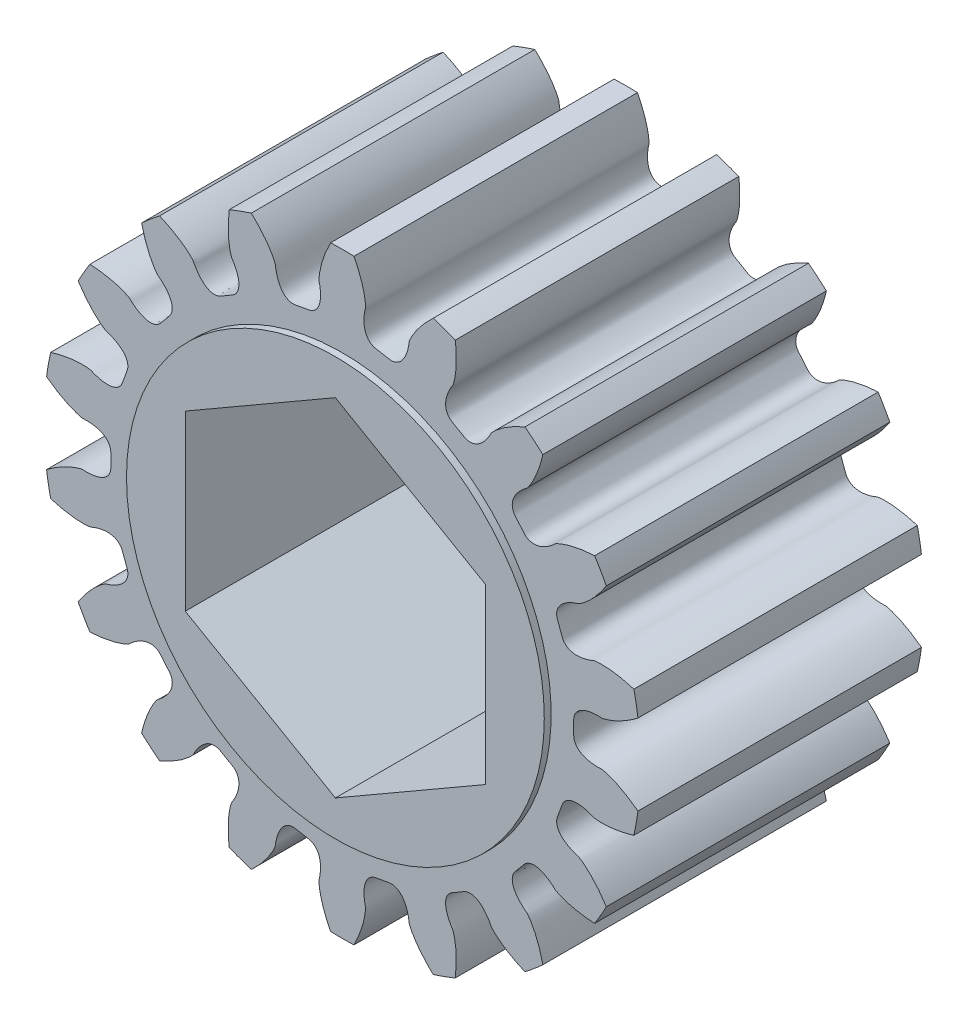
SolidWorks part; units mm, degrees
material "7075-T6 (SN)"
ref_plane "Front Plane" through (0, 0, 0) normal (0, 0, 1) x (1, 0, 0)
ref_plane "Top Plane" through (0, 0, 0) normal (0, 1, 0) x (1, 0, 0)
ref_plane "Right Plane" through (0, 0, 0) normal (1, 0, 0) x (0, 0, -1)
ref_plane "Plane1" through (0, 0, 6.0325) normal (0, 0, 1) x (1, 0, 0)
sketch "Sketch1" plane through (0, 0, 6.0325) normal (0, 0, 1) x (1, 0, 0)
  arc A0 (12.411, -2.694) -> (12.5839, -1.7132) centre (0, 0) ccw
  arc A1 (12.5839, 1.7132) -> (12.411, 2.694) centre (0, 0) ccw
  arc A2 (11.239, 5.9139) -> (10.7411, 6.7764) centre (0, 0) ccw
  arc A3 (8.5386, 9.4012) -> (7.7757, 10.0414) centre (0, 0) ccw
  arc A4 (4.8082, 11.7546) -> (3.8724, 12.0952) centre (0, 0) ccw
  arc A5 (0.498, 12.6902) -> (-0.498, 12.6902) centre (0, 0) ccw
  arc A6 (-3.8724, 12.0952) -> (-4.8082, 11.7546) centre (0, 0) ccw
  arc A7 (-7.7757, 10.0414) -> (-8.5386, 9.4012) centre (0, 0) ccw
  arc A8 (-10.7411, 6.7764) -> (-11.239, 5.9139) centre (0, 0) ccw
  arc A9 (-12.411, 2.694) -> (-12.5839, 1.7132) centre (0, 0) ccw
  arc A10 (-12.5839, -1.7132) -> (-12.411, -2.694) centre (0, 0) ccw
  arc A11 (-11.239, -5.9139) -> (-10.7411, -6.7764) centre (0, 0) ccw
  arc A12 (-8.5386, -9.4012) -> (-7.7757, -10.0414) centre (0, 0) ccw
  arc A13 (-4.8082, -11.7546) -> (-3.8724, -12.0952) centre (0, 0) ccw
  arc A14 (-0.498, -12.6902) -> (0.498, -12.6902) centre (0, 0) ccw
  arc A15 (3.8724, -12.0952) -> (4.8082, -11.7546) centre (0, 0) ccw
  arc A16 (7.7757, -10.0414) -> (8.5386, -9.4012) centre (0, 0) ccw
  arc A17 (10.7411, -6.7764) -> (11.239, -5.9139) centre (0, 0) ccw
  spline S0 degree 3 poles (11.239, -5.9139) (11.1509, -5.7775) (11.0298, -5.6051) (10.8706, -5.4047) (10.783, -5.3007) (10.6983, -5.2057) (10.6171, -5.1195) (10.5396, -5.0419) (10.4664, -4.9725) (10.3977, -4.911) (10.3341, -4.8571) (10.2759, -4.8106) (10.2233, -4.771) (10.1769, -4.7378) (10.1275, -4.7053) (10.0518, -4.6541) (9.95, -4.6355) (9.8549, -4.5968) (9.7835, -4.5675) (9.7159, -4.5362) (9.6517, -4.5038) (9.5908, -4.4699) (9.5333, -4.4347) (9.479, -4.3981) (9.4279, -4.3599) (9.3799, -4.3199) (9.3348, -4.2779) (9.2928, -4.2333) (9.2539, -4.1857) (9.2182, -4.1342) (9.1862, -4.078) (9.1588, -4.016) (9.1377, -3.9474) (9.125, -3.8716) (9.1237, -3.7895) (9.1359, -3.7108) (9.1798, -3.5695) (9.267, -3.3729) (9.3266, -3.1663) (9.3837, -3.0298) (9.425, -2.9616) (9.4787, -2.8996) (9.5372, -2.8497) (9.5975, -2.8107) (9.6583, -2.7808) (9.719, -2.7583) (9.7794, -2.7419) (9.8398, -2.7304) (9.9007, -2.7233) (9.9622, -2.72) (10.0247, -2.7203) (10.0884, -2.7238) (10.1535, -2.7307) (10.2202, -2.7407) (10.2886, -2.7539) (10.3586, -2.7703) (10.4305, -2.7899) (10.504, -2.8133) (10.6018, -2.8447) (10.6917, -2.8959) (10.7827, -2.9054) (10.8413, -2.9122) (10.8982, -2.9166) (10.9639, -2.9201) (11.0385, -2.9219) (11.1219, -2.9215) (11.2139, -2.9185) (11.3147, -2.9124) (11.4239, -2.9027) (11.5416, -2.889) (11.6675, -2.8706) (11.8014, -2.8472) (12.0522, -2.7961) (12.2559, -2.7418) (12.411, -2.694) knots 0 0 0 0 0.068568 0.088955 0.108106 0.126021 0.142701 0.158145 0.172354 0.185328 0.197065 0.207567 0.216834 0.224865 0.231661 0.241836 0.263156 0.274398 0.285253 0.295736 0.305862 0.315655 0.325139 0.334346 0.343315 0.352092 0.360737 0.369325 0.377945 0.38671 0.395752 0.405223 0.415278 0.426045 0.437578 0.449793 0.459544 0.5 0.540456 0.550207 0.562422 0.573955 0.584722 0.594777 0.604248 0.61329 0.622055 0.630675 0.639263 0.647908 0.656685 0.665654 0.674861 0.684345 0.694138 0.704264 0.714747 0.725602 0.736844 0.758164 0.768339 0.775135 0.783166 0.792433 0.802935 0.814672 0.827646 0.841855 0.857299 0.873979 0.891894 0.911045 0.931432 1 1 1 1
  spline S1 degree 3 poles (12.5839, -1.7132) (12.4545, -1.6153) (12.2817, -1.4946) (12.0635, -1.3608) (11.9456, -1.293) (11.8336, -1.2327) (11.7278, -1.1795) (11.6284, -1.133) (11.5359, -1.0929) (11.4503, -1.0586) (11.3721, -1.0297) (11.3015, -1.0059) (11.2385, -0.9867) (11.1836, -0.9714) (11.1261, -0.9577) (11.0374, -0.9355) (10.9354, -0.9529) (10.8328, -0.949) (10.7557, -0.9458) (10.6815, -0.9396) (10.61, -0.9311) (10.5412, -0.9201) (10.4751, -0.9067) (10.4116, -0.8909) (10.3505, -0.8724) (10.2917, -0.8513) (10.235, -0.8272) (10.1803, -0.7997) (10.1274, -0.7682) (10.0762, -0.7321) (10.027, -0.6902) (9.9801, -0.6413) (9.9367, -0.584) (9.8988, -0.5172) (9.8696, -0.4405) (9.8541, -0.3623) (9.847, -0.2145) (9.8618, 0) (9.847, 0.2145) (9.8541, 0.3623) (9.8696, 0.4405) (9.8988, 0.5172) (9.9367, 0.584) (9.9801, 0.6413) (10.027, 0.6902) (10.0762, 0.7321) (10.1274, 0.7682) (10.1803, 0.7997) (10.235, 0.8272) (10.2917, 0.8513) (10.3505, 0.8724) (10.4116, 0.8909) (10.4751, 0.9067) (10.5412, 0.9201) (10.61, 0.9311) (10.6815, 0.9396) (10.7557, 0.9458) (10.8328, 0.949) (10.9354, 0.9529) (11.0374, 0.9355) (11.1261, 0.9577) (11.1836, 0.9714) (11.2385, 0.9867) (11.3015, 1.0059) (11.3721, 1.0297) (11.4503, 1.0586) (11.5359, 1.0929) (11.6284, 1.133) (11.7278, 1.1795) (11.8336, 1.2327) (11.9456, 1.293) (12.0635, 1.3608) (12.2817, 1.4946) (12.4545, 1.6153) (12.5839, 1.7132) knots 0 0 0 0 0.068568 0.088955 0.108106 0.126021 0.142701 0.158145 0.172354 0.185328 0.197065 0.207567 0.216834 0.224865 0.231661 0.241836 0.263156 0.274398 0.285253 0.295736 0.305862 0.315655 0.325139 0.334346 0.343315 0.352092 0.360737 0.369325 0.377945 0.38671 0.395752 0.405223 0.415278 0.426045 0.437578 0.449793 0.459544 0.5 0.540456 0.550207 0.562422 0.573955 0.584722 0.594777 0.604248 0.61329 0.622055 0.630675 0.639263 0.647908 0.656685 0.665654 0.674861 0.684345 0.694138 0.704264 0.714747 0.725602 0.736844 0.758164 0.768339 0.775135 0.783166 0.792433 0.802935 0.814672 0.827646 0.841855 0.857299 0.873979 0.891894 0.911045 0.931432 1 1 1 1
  spline S2 degree 3 poles (12.411, 2.694) (12.2559, 2.7418) (12.0522, 2.7961) (11.8014, 2.8472) (11.6675, 2.8706) (11.5416, 2.889) (11.4239, 2.9027) (11.3147, 2.9124) (11.2139, 2.9185) (11.1219, 2.9215) (11.0385, 2.9219) (10.9639, 2.9201) (10.8982, 2.9166) (10.8413, 2.9122) (10.7827, 2.9054) (10.6917, 2.8959) (10.6018, 2.8447) (10.504, 2.8133) (10.4305, 2.7899) (10.3586, 2.7703) (10.2886, 2.7539) (10.2202, 2.7407) (10.1535, 2.7307) (10.0884, 2.7238) (10.0247, 2.7203) (9.9622, 2.72) (9.9007, 2.7233) (9.8398, 2.7304) (9.7794, 2.7419) (9.719, 2.7583) (9.6583, 2.7808) (9.5975, 2.8107) (9.5372, 2.8497) (9.4787, 2.8996) (9.425, 2.9616) (9.3837, 3.0298) (9.3266, 3.1663) (9.267, 3.3729) (9.1798, 3.5695) (9.1359, 3.7108) (9.1237, 3.7895) (9.125, 3.8716) (9.1377, 3.9474) (9.1588, 4.016) (9.1862, 4.078) (9.2182, 4.1342) (9.2539, 4.1857) (9.2928, 4.2333) (9.3348, 4.2779) (9.3799, 4.3199) (9.4279, 4.3599) (9.479, 4.3981) (9.5333, 4.4347) (9.5908, 4.4699) (9.6517, 4.5038) (9.7159, 4.5362) (9.7835, 4.5675) (9.8549, 4.5968) (9.95, 4.6355) (10.0518, 4.6541) (10.1275, 4.7053) (10.1769, 4.7378) (10.2233, 4.771) (10.2759, 4.8106) (10.3341, 4.8571) (10.3977, 4.911) (10.4664, 4.9725) (10.5396, 5.0419) (10.6171, 5.1195) (10.6983, 5.2057) (10.783, 5.3007) (10.8706, 5.4047) (11.0298, 5.6051) (11.1509, 5.7775) (11.239, 5.9139) knots 0 0 0 0 0.068568 0.088955 0.108106 0.126021 0.142701 0.158145 0.172354 0.185328 0.197065 0.207567 0.216834 0.224865 0.231661 0.241836 0.263156 0.274398 0.285253 0.295736 0.305862 0.315655 0.325139 0.334346 0.343315 0.352092 0.360737 0.369325 0.377945 0.38671 0.395752 0.405223 0.415278 0.426045 0.437578 0.449793 0.459544 0.5 0.540456 0.550207 0.562422 0.573955 0.584722 0.594777 0.604248 0.61329 0.622055 0.630675 0.639263 0.647908 0.656685 0.665654 0.674861 0.684345 0.694138 0.704264 0.714747 0.725602 0.736844 0.758164 0.768339 0.775135 0.783166 0.792433 0.802935 0.814672 0.827646 0.841855 0.857299 0.873979 0.891894 0.911045 0.931432 1 1 1 1
  spline S3 degree 3 poles (10.7411, 6.7764) (10.579, 6.7682) (10.369, 6.7496) (10.1159, 6.7118) (9.982, 6.688) (9.8574, 6.6622) (9.7422, 6.6349) (9.6362, 6.6066) (9.5395, 6.5779) (9.4519, 6.5492) (9.3735, 6.521) (9.304, 6.4939) (9.2434, 6.4682) (9.1915, 6.4445) (9.1387, 6.418) (9.0565, 6.3781) (8.9895, 6.2992) (8.9084, 6.2362) (8.8473, 6.1891) (8.7864, 6.1461) (8.7262, 6.1067) (8.6665, 6.0709) (8.6073, 6.0387) (8.5484, 6.01) (8.4897, 5.9848) (8.4311, 5.9632) (8.3722, 5.9453) (8.3126, 5.9312) (8.2518, 5.9212) (8.1894, 5.916) (8.1248, 5.9165) (8.0574, 5.9238) (7.9873, 5.9398) (7.9154, 5.9667) (7.8437, 6.0066) (7.7815, 6.0565) (7.6812, 6.1652) (7.5546, 6.339) (7.4054, 6.4939) (7.3157, 6.6116) (7.2774, 6.6815) (7.2505, 6.759) (7.2365, 6.8346) (7.2329, 6.9064) (7.2374, 6.974) (7.2483, 7.0377) (7.2642, 7.0983) (7.2845, 7.1563) (7.3088, 7.2126) (7.3367, 7.2675) (7.3681, 7.3215) (7.4031, 7.3749) (7.4416, 7.4279) (7.4836, 7.4806) (7.5292, 7.5332) (7.5785, 7.5857) (7.6314, 7.6382) (7.6884, 7.6901) (7.7645, 7.7591) (7.8538, 7.8113) (7.9074, 7.8854) (7.9427, 7.9328) (7.975, 7.9798) (8.0108, 8.035) (8.0497, 8.0987) (8.091, 8.1711) (8.1345, 8.2523) (8.1796, 8.3426) (8.2258, 8.442) (8.2727, 8.5508) (8.3198, 8.669) (8.3665, 8.7967) (8.4476, 9.0394) (8.5024, 9.243) (8.5386, 9.4012) knots 0 0 0 0 0.068568 0.088955 0.108106 0.126021 0.142701 0.158145 0.172354 0.185328 0.197065 0.207567 0.216834 0.224865 0.231661 0.241836 0.263156 0.274398 0.285253 0.295736 0.305862 0.315655 0.325139 0.334346 0.343315 0.352092 0.360737 0.369325 0.377945 0.38671 0.395752 0.405223 0.415278 0.426045 0.437578 0.449793 0.459544 0.5 0.540456 0.550207 0.562422 0.573955 0.584722 0.594777 0.604248 0.61329 0.622055 0.630675 0.639263 0.647908 0.656685 0.665654 0.674861 0.684345 0.694138 0.704264 0.714747 0.725602 0.736844 0.758164 0.768339 0.775135 0.783166 0.792433 0.802935 0.814672 0.827646 0.841855 0.857299 0.873979 0.891894 0.911045 0.931432 1 1 1 1
  spline S4 degree 3 poles (7.7757, 10.0414) (7.6261, 9.9783) (7.4352, 9.889) (7.2103, 9.7669) (7.0926, 9.6987) (6.9844, 9.6318) (6.8854, 9.5668) (6.7955, 9.504) (6.7144, 9.4439) (6.6419, 9.387) (6.5778, 9.3337) (6.5219, 9.2844) (6.4737, 9.2395) (6.433, 9.1996) (6.3925, 9.1566) (6.3289, 9.0909) (6.2929, 8.9939) (6.2382, 8.907) (6.197, 8.8418) (6.1544, 8.7806) (6.1113, 8.723) (6.0675, 8.6689) (6.0228, 8.6184) (5.9773, 8.5713) (5.9308, 8.5276) (5.8831, 8.4872) (5.8339, 8.4502) (5.7827, 8.4166) (5.729, 8.3865) (5.6721, 8.3602) (5.6112, 8.3385) (5.5455, 8.3223) (5.4741, 8.3134) (5.3973, 8.3141) (5.3163, 8.327) (5.2408, 8.3527) (5.1093, 8.4205) (4.9309, 8.5405) (4.7377, 8.6351) (4.6132, 8.715) (4.5533, 8.7675) (4.5016, 8.8312) (4.4626, 8.8974) (4.4346, 8.9637) (4.4157, 9.0287) (4.4041, 9.0923) (4.3984, 9.1547) (4.3976, 9.2162) (4.4012, 9.2774) (4.4086, 9.3385) (4.4197, 9.4) (4.4343, 9.4621) (4.4523, 9.5251) (4.4738, 9.589) (4.4987, 9.6541) (4.527, 9.7202) (4.5587, 9.7876) (4.5945, 9.8559) (4.6425, 9.9467) (4.7085, 10.0264) (4.7336, 10.1143) (4.7506, 10.1709) (4.7648, 10.2262) (4.7796, 10.2903) (4.7943, 10.3634) (4.8084, 10.4456) (4.8215, 10.5368) (4.833, 10.637) (4.8424, 10.7463) (4.8492, 10.8646) (4.853, 10.9917) (4.8533, 11.1277) (4.8465, 11.3836) (4.8284, 11.5935) (4.8082, 11.7546) knots 0 0 0 0 0.068568 0.088955 0.108106 0.126021 0.142701 0.158145 0.172354 0.185328 0.197065 0.207567 0.216834 0.224865 0.231661 0.241836 0.263156 0.274398 0.285253 0.295736 0.305862 0.315655 0.325139 0.334346 0.343315 0.352092 0.360737 0.369325 0.377945 0.38671 0.395752 0.405223 0.415278 0.426045 0.437578 0.449793 0.459544 0.5 0.540456 0.550207 0.562422 0.573955 0.584722 0.594777 0.604248 0.61329 0.622055 0.630675 0.639263 0.647908 0.656685 0.665654 0.674861 0.684345 0.694138 0.704264 0.714747 0.725602 0.736844 0.758164 0.768339 0.775135 0.783166 0.792433 0.802935 0.814672 0.827646 0.841855 0.857299 0.873979 0.891894 0.911045 0.931432 1 1 1 1
  spline S5 degree 3 poles (3.8724, 12.0952) (3.7534, 11.9848) (3.6046, 11.8356) (3.435, 11.644) (3.3477, 11.5396) (3.2689, 11.4398) (3.1981, 11.3448) (3.1351, 11.255) (3.0794, 11.1708) (3.0308, 11.0926) (2.9888, 11.0205) (2.9531, 10.9551) (2.9232, 10.8965) (2.8986, 10.845) (2.8752, 10.7907) (2.8379, 10.7073) (2.8373, 10.6038) (2.8157, 10.5034) (2.7992, 10.428) (2.7801, 10.356) (2.7593, 10.2871) (2.7366, 10.2213) (2.7119, 10.1586) (2.6853, 10.0987) (2.6565, 10.0418) (2.6255, 9.9875) (2.5919, 9.9359) (2.5553, 9.8868) (2.5152, 9.8401) (2.4707, 9.796) (2.4209, 9.7548) (2.3646, 9.7171) (2.3006, 9.6843) (2.2282, 9.6587) (2.1477, 9.6431) (2.068, 9.6414) (1.9212, 9.6602) (1.7125, 9.7119) (1.4986, 9.7347) (1.3543, 9.7673) (1.28, 9.7961) (1.2096, 9.8383) (1.1503, 9.8871) (1.1014, 9.9398) (1.0614, 9.9945) (1.0287, 10.0503) (1.002, 10.1069) (0.9803, 10.1645) (0.9627, 10.2231) (0.9488, 10.2832) (0.9382, 10.3447) (0.9306, 10.4081) (0.926, 10.4735) (0.9243, 10.5409) (0.9255, 10.6105) (0.9295, 10.6823) (0.9362, 10.7565) (0.9465, 10.833) (0.9605, 10.9347) (0.9953, 11.0321) (0.9888, 11.1233) (0.9854, 11.1823) (0.9799, 11.2391) (0.9719, 11.3044) (0.9607, 11.3782) (0.9458, 11.4602) (0.9269, 11.5504) (0.9034, 11.6485) (0.8749, 11.7544) (0.8409, 11.8679) (0.801, 11.9887) (0.7547, 12.1166) (0.6608, 12.3546) (0.572, 12.5458) (0.498, 12.6902) knots 0 0 0 0 0.068568 0.088955 0.108106 0.126021 0.142701 0.158145 0.172354 0.185328 0.197065 0.207567 0.216834 0.224865 0.231661 0.241836 0.263156 0.274398 0.285253 0.295736 0.305862 0.315655 0.325139 0.334346 0.343315 0.352092 0.360737 0.369325 0.377945 0.38671 0.395752 0.405223 0.415278 0.426045 0.437578 0.449793 0.459544 0.5 0.540456 0.550207 0.562422 0.573955 0.584722 0.594777 0.604248 0.61329 0.622055 0.630675 0.639263 0.647908 0.656685 0.665654 0.674861 0.684345 0.694138 0.704264 0.714747 0.725602 0.736844 0.758164 0.768339 0.775135 0.783166 0.792433 0.802935 0.814672 0.827646 0.841855 0.857299 0.873979 0.891894 0.911045 0.931432 1 1 1 1
  spline S6 degree 3 poles (-0.498, 12.6902) (-0.572, 12.5458) (-0.6608, 12.3546) (-0.7547, 12.1166) (-0.801, 11.9887) (-0.8409, 11.8679) (-0.8749, 11.7544) (-0.9034, 11.6485) (-0.9269, 11.5504) (-0.9458, 11.4602) (-0.9607, 11.3782) (-0.9719, 11.3044) (-0.9799, 11.2391) (-0.9854, 11.1823) (-0.9888, 11.1233) (-0.9953, 11.0321) (-0.9605, 10.9347) (-0.9465, 10.833) (-0.9362, 10.7565) (-0.9295, 10.6823) (-0.9255, 10.6105) (-0.9243, 10.5409) (-0.926, 10.4735) (-0.9306, 10.4081) (-0.9382, 10.3447) (-0.9488, 10.2832) (-0.9627, 10.2231) (-0.9803, 10.1645) (-1.002, 10.1069) (-1.0287, 10.0503) (-1.0614, 9.9945) (-1.1014, 9.9398) (-1.1503, 9.8871) (-1.2096, 9.8383) (-1.28, 9.7961) (-1.3543, 9.7673) (-1.4986, 9.7347) (-1.7125, 9.7119) (-1.9212, 9.6602) (-2.068, 9.6414) (-2.1477, 9.6431) (-2.2282, 9.6587) (-2.3006, 9.6843) (-2.3646, 9.7171) (-2.4209, 9.7548) (-2.4707, 9.796) (-2.5152, 9.8401) (-2.5553, 9.8868) (-2.5919, 9.9359) (-2.6255, 9.9875) (-2.6565, 10.0418) (-2.6853, 10.0987) (-2.7119, 10.1586) (-2.7366, 10.2213) (-2.7593, 10.2871) (-2.7801, 10.356) (-2.7992, 10.428) (-2.8157, 10.5034) (-2.8373, 10.6038) (-2.8379, 10.7073) (-2.8752, 10.7907) (-2.8986, 10.845) (-2.9232, 10.8965) (-2.9531, 10.9551) (-2.9888, 11.0205) (-3.0308, 11.0926) (-3.0794, 11.1708) (-3.1351, 11.255) (-3.1981, 11.3448) (-3.2689, 11.4398) (-3.3477, 11.5396) (-3.435, 11.644) (-3.6046, 11.8356) (-3.7534, 11.9848) (-3.8724, 12.0952) knots 0 0 0 0 0.068568 0.088955 0.108106 0.126021 0.142701 0.158145 0.172354 0.185328 0.197065 0.207567 0.216834 0.224865 0.231661 0.241836 0.263156 0.274398 0.285253 0.295736 0.305862 0.315655 0.325139 0.334346 0.343315 0.352092 0.360737 0.369325 0.377945 0.38671 0.395752 0.405223 0.415278 0.426045 0.437578 0.449793 0.459544 0.5 0.540456 0.550207 0.562422 0.573955 0.584722 0.594777 0.604248 0.61329 0.622055 0.630675 0.639263 0.647908 0.656685 0.665654 0.674861 0.684345 0.694138 0.704264 0.714747 0.725602 0.736844 0.758164 0.768339 0.775135 0.783166 0.792433 0.802935 0.814672 0.827646 0.841855 0.857299 0.873979 0.891894 0.911045 0.931432 1 1 1 1
  spline S7 degree 3 poles (-4.8082, 11.7546) (-4.8284, 11.5935) (-4.8465, 11.3836) (-4.8533, 11.1277) (-4.853, 10.9917) (-4.8492, 10.8646) (-4.8424, 10.7463) (-4.833, 10.637) (-4.8215, 10.5368) (-4.8084, 10.4456) (-4.7943, 10.3634) (-4.7796, 10.2903) (-4.7648, 10.2262) (-4.7506, 10.1709) (-4.7336, 10.1143) (-4.7085, 10.0264) (-4.6425, 9.9467) (-4.5945, 9.8559) (-4.5587, 9.7876) (-4.527, 9.7202) (-4.4987, 9.6541) (-4.4738, 9.589) (-4.4523, 9.5251) (-4.4343, 9.4621) (-4.4197, 9.4) (-4.4086, 9.3385) (-4.4012, 9.2774) (-4.3976, 9.2162) (-4.3984, 9.1547) (-4.4041, 9.0923) (-4.4157, 9.0287) (-4.4346, 8.9637) (-4.4626, 8.8974) (-4.5016, 8.8312) (-4.5533, 8.7675) (-4.6132, 8.715) (-4.7377, 8.6351) (-4.9309, 8.5405) (-5.1093, 8.4205) (-5.2408, 8.3527) (-5.3163, 8.327) (-5.3973, 8.3141) (-5.4741, 8.3134) (-5.5455, 8.3223) (-5.6112, 8.3385) (-5.6721, 8.3602) (-5.729, 8.3865) (-5.7827, 8.4166) (-5.8339, 8.4502) (-5.8831, 8.4872) (-5.9308, 8.5276) (-5.9773, 8.5713) (-6.0228, 8.6184) (-6.0675, 8.6689) (-6.1113, 8.723) (-6.1544, 8.7806) (-6.197, 8.8418) (-6.2382, 8.907) (-6.2929, 8.9939) (-6.3289, 9.0909) (-6.3925, 9.1566) (-6.433, 9.1996) (-6.4737, 9.2395) (-6.5219, 9.2844) (-6.5778, 9.3337) (-6.6419, 9.387) (-6.7144, 9.4439) (-6.7954, 9.504) (-6.8854, 9.5668) (-6.9844, 9.6318) (-7.0926, 9.6987) (-7.2103, 9.7669) (-7.4352, 9.889) (-7.6261, 9.9783) (-7.7757, 10.0414) knots 0 0 0 0 0.068568 0.088955 0.108106 0.126021 0.142701 0.158145 0.172354 0.185328 0.197065 0.207567 0.216834 0.224865 0.231661 0.241836 0.263156 0.274398 0.285253 0.295736 0.305862 0.315655 0.325139 0.334346 0.343315 0.352092 0.360737 0.369325 0.377945 0.38671 0.395752 0.405223 0.415278 0.426045 0.437578 0.449793 0.459544 0.5 0.540456 0.550207 0.562422 0.573955 0.584722 0.594777 0.604248 0.61329 0.622055 0.630675 0.639263 0.647908 0.656685 0.665654 0.674861 0.684345 0.694138 0.704264 0.714747 0.725602 0.736844 0.758164 0.768339 0.775135 0.783166 0.792433 0.802935 0.814672 0.827646 0.841855 0.857299 0.873979 0.891894 0.911045 0.931432 1 1 1 1
  spline S8 degree 3 poles (-8.5386, 9.4012) (-8.5024, 9.243) (-8.4476, 9.0394) (-8.3665, 8.7967) (-8.3198, 8.669) (-8.2727, 8.5508) (-8.2258, 8.442) (-8.1796, 8.3426) (-8.1345, 8.2523) (-8.091, 8.1711) (-8.0497, 8.0987) (-8.0108, 8.035) (-7.975, 7.9798) (-7.9427, 7.9328) (-7.9074, 7.8854) (-7.8538, 7.8113) (-7.7645, 7.7591) (-7.6884, 7.6901) (-7.6314, 7.6382) (-7.5785, 7.5857) (-7.5292, 7.5332) (-7.4836, 7.4806) (-7.4416, 7.4279) (-7.4031, 7.3749) (-7.3681, 7.3215) (-7.3367, 7.2675) (-7.3088, 7.2126) (-7.2845, 7.1563) (-7.2642, 7.0983) (-7.2483, 7.0377) (-7.2374, 6.974) (-7.2329, 6.9064) (-7.2365, 6.8346) (-7.2505, 6.759) (-7.2774, 6.6815) (-7.3157, 6.6116) (-7.4054, 6.4939) (-7.5546, 6.339) (-7.6812, 6.1652) (-7.7815, 6.0565) (-7.8437, 6.0066) (-7.9154, 5.9667) (-7.9873, 5.9398) (-8.0574, 5.9238) (-8.1248, 5.9165) (-8.1894, 5.916) (-8.2518, 5.9212) (-8.3126, 5.9312) (-8.3722, 5.9453) (-8.4311, 5.9632) (-8.4897, 5.9848) (-8.5484, 6.01) (-8.6073, 6.0387) (-8.6665, 6.0709) (-8.7262, 6.1067) (-8.7864, 6.1461) (-8.8473, 6.1891) (-8.9084, 6.2362) (-8.9895, 6.2992) (-9.0565, 6.3781) (-9.1387, 6.418) (-9.1915, 6.4445) (-9.2434, 6.4682) (-9.304, 6.4939) (-9.3735, 6.521) (-9.4519, 6.5492) (-9.5395, 6.5779) (-9.6362, 6.6066) (-9.7422, 6.6349) (-9.8574, 6.6622) (-9.982, 6.688) (-10.1159, 6.7118) (-10.369, 6.7496) (-10.579, 6.7682) (-10.7411, 6.7764) knots 0 0 0 0 0.068568 0.088955 0.108106 0.126021 0.142701 0.158145 0.172354 0.185328 0.197065 0.207567 0.216834 0.224865 0.231661 0.241836 0.263156 0.274398 0.285253 0.295736 0.305862 0.315655 0.325139 0.334346 0.343315 0.352092 0.360737 0.369325 0.377945 0.38671 0.395752 0.405223 0.415278 0.426045 0.437578 0.449793 0.459544 0.5 0.540456 0.550207 0.562422 0.573955 0.584722 0.594777 0.604248 0.61329 0.622055 0.630675 0.639263 0.647908 0.656685 0.665654 0.674861 0.684345 0.694138 0.704264 0.714747 0.725602 0.736844 0.758164 0.768339 0.775135 0.783166 0.792433 0.802935 0.814672 0.827646 0.841855 0.857299 0.873979 0.891894 0.911045 0.931432 1 1 1 1
  spline S9 degree 3 poles (-11.239, 5.9139) (-11.1509, 5.7775) (-11.0298, 5.6051) (-10.8706, 5.4047) (-10.783, 5.3007) (-10.6983, 5.2057) (-10.6171, 5.1195) (-10.5396, 5.0419) (-10.4664, 4.9725) (-10.3977, 4.911) (-10.3341, 4.8571) (-10.2759, 4.8106) (-10.2233, 4.771) (-10.1769, 4.7378) (-10.1275, 4.7053) (-10.0518, 4.6541) (-9.95, 4.6355) (-9.8549, 4.5968) (-9.7835, 4.5675) (-9.7159, 4.5362) (-9.6517, 4.5038) (-9.5908, 4.4699) (-9.5333, 4.4347) (-9.479, 4.3981) (-9.4279, 4.3599) (-9.3799, 4.3199) (-9.3348, 4.2779) (-9.2928, 4.2333) (-9.2539, 4.1857) (-9.2182, 4.1342) (-9.1862, 4.078) (-9.1588, 4.016) (-9.1377, 3.9474) (-9.125, 3.8716) (-9.1237, 3.7895) (-9.1359, 3.7108) (-9.1798, 3.5695) (-9.267, 3.3729) (-9.3266, 3.1663) (-9.3837, 3.0298) (-9.425, 2.9616) (-9.4787, 2.8996) (-9.5372, 2.8497) (-9.5975, 2.8107) (-9.6583, 2.7808) (-9.719, 2.7583) (-9.7794, 2.7419) (-9.8398, 2.7304) (-9.9007, 2.7233) (-9.9622, 2.72) (-10.0247, 2.7203) (-10.0884, 2.7238) (-10.1535, 2.7307) (-10.2202, 2.7407) (-10.2886, 2.7539) (-10.3586, 2.7703) (-10.4305, 2.7899) (-10.504, 2.8133) (-10.6018, 2.8447) (-10.6917, 2.8959) (-10.7827, 2.9054) (-10.8413, 2.9122) (-10.8982, 2.9166) (-10.9639, 2.9201) (-11.0385, 2.9219) (-11.1219, 2.9215) (-11.2139, 2.9185) (-11.3147, 2.9124) (-11.4239, 2.9027) (-11.5416, 2.889) (-11.6675, 2.8706) (-11.8014, 2.8472) (-12.0522, 2.7961) (-12.2559, 2.7418) (-12.411, 2.694) knots 0 0 0 0 0.068568 0.088955 0.108106 0.126021 0.142701 0.158145 0.172354 0.185328 0.197065 0.207567 0.216834 0.224865 0.231661 0.241836 0.263156 0.274398 0.285253 0.295736 0.305862 0.315655 0.325139 0.334346 0.343315 0.352092 0.360737 0.369325 0.377945 0.38671 0.395752 0.405223 0.415278 0.426045 0.437578 0.449793 0.459544 0.5 0.540456 0.550207 0.562422 0.573955 0.584722 0.594777 0.604248 0.61329 0.622055 0.630675 0.639263 0.647908 0.656685 0.665654 0.674861 0.684345 0.694138 0.704264 0.714747 0.725602 0.736844 0.758164 0.768339 0.775135 0.783166 0.792433 0.802935 0.814672 0.827646 0.841855 0.857299 0.873979 0.891894 0.911045 0.931432 1 1 1 1
  spline S10 degree 3 poles (-12.5839, 1.7132) (-12.4545, 1.6153) (-12.2817, 1.4946) (-12.0635, 1.3608) (-11.9456, 1.293) (-11.8336, 1.2327) (-11.7278, 1.1795) (-11.6284, 1.133) (-11.5359, 1.0929) (-11.4503, 1.0586) (-11.3721, 1.0297) (-11.3015, 1.0059) (-11.2385, 0.9867) (-11.1836, 0.9714) (-11.1261, 0.9577) (-11.0374, 0.9355) (-10.9354, 0.9529) (-10.8328, 0.949) (-10.7557, 0.9458) (-10.6815, 0.9396) (-10.61, 0.9311) (-10.5412, 0.9201) (-10.4751, 0.9067) (-10.4116, 0.8909) (-10.3505, 0.8724) (-10.2917, 0.8513) (-10.235, 0.8272) (-10.1803, 0.7997) (-10.1274, 0.7682) (-10.0762, 0.7321) (-10.027, 0.6902) (-9.9801, 0.6413) (-9.9367, 0.584) (-9.8988, 0.5172) (-9.8696, 0.4405) (-9.8541, 0.3623) (-9.847, 0.2145) (-9.8618, 0) (-9.847, -0.2145) (-9.8541, -0.3623) (-9.8696, -0.4405) (-9.8988, -0.5172) (-9.9367, -0.584) (-9.9801, -0.6413) (-10.027, -0.6902) (-10.0762, -0.7321) (-10.1274, -0.7682) (-10.1803, -0.7997) (-10.235, -0.8272) (-10.2917, -0.8513) (-10.3505, -0.8724) (-10.4116, -0.8909) (-10.4751, -0.9067) (-10.5412, -0.9201) (-10.61, -0.9311) (-10.6815, -0.9396) (-10.7557, -0.9458) (-10.8328, -0.949) (-10.9354, -0.9529) (-11.0374, -0.9355) (-11.1261, -0.9577) (-11.1836, -0.9714) (-11.2385, -0.9867) (-11.3015, -1.0059) (-11.3721, -1.0297) (-11.4503, -1.0586) (-11.5359, -1.0929) (-11.6284, -1.133) (-11.7278, -1.1795) (-11.8336, -1.2327) (-11.9456, -1.293) (-12.0635, -1.3608) (-12.2817, -1.4946) (-12.4545, -1.6153) (-12.5839, -1.7132) knots 0 0 0 0 0.068568 0.088955 0.108106 0.126021 0.142701 0.158145 0.172354 0.185328 0.197065 0.207567 0.216834 0.224865 0.231661 0.241836 0.263156 0.274398 0.285253 0.295736 0.305862 0.315655 0.325139 0.334346 0.343315 0.352092 0.360737 0.369325 0.377945 0.38671 0.395752 0.405223 0.415278 0.426045 0.437578 0.449793 0.459544 0.5 0.540456 0.550207 0.562422 0.573955 0.584722 0.594777 0.604248 0.61329 0.622055 0.630675 0.639263 0.647908 0.656685 0.665654 0.674861 0.684345 0.694138 0.704264 0.714747 0.725602 0.736844 0.758164 0.768339 0.775135 0.783166 0.792433 0.802935 0.814672 0.827646 0.841855 0.857299 0.873979 0.891894 0.911045 0.931432 1 1 1 1
  spline S11 degree 3 poles (-12.411, -2.694) (-12.2559, -2.7418) (-12.0522, -2.7961) (-11.8014, -2.8472) (-11.6675, -2.8706) (-11.5416, -2.889) (-11.4239, -2.9027) (-11.3147, -2.9124) (-11.2139, -2.9185) (-11.1219, -2.9215) (-11.0385, -2.9219) (-10.9639, -2.9201) (-10.8982, -2.9166) (-10.8413, -2.9122) (-10.7827, -2.9054) (-10.6917, -2.8959) (-10.6018, -2.8447) (-10.504, -2.8133) (-10.4305, -2.7899) (-10.3586, -2.7703) (-10.2886, -2.7539) (-10.2202, -2.7407) (-10.1535, -2.7307) (-10.0884, -2.7238) (-10.0247, -2.7203) (-9.9622, -2.72) (-9.9007, -2.7233) (-9.8398, -2.7304) (-9.7794, -2.7419) (-9.719, -2.7583) (-9.6583, -2.7808) (-9.5975, -2.8107) (-9.5372, -2.8497) (-9.4787, -2.8996) (-9.425, -2.9616) (-9.3837, -3.0298) (-9.3266, -3.1663) (-9.267, -3.3729) (-9.1798, -3.5695) (-9.1359, -3.7108) (-9.1237, -3.7895) (-9.125, -3.8716) (-9.1377, -3.9474) (-9.1588, -4.016) (-9.1862, -4.078) (-9.2182, -4.1342) (-9.2539, -4.1857) (-9.2928, -4.2333) (-9.3348, -4.2779) (-9.3799, -4.3199) (-9.4279, -4.3599) (-9.479, -4.3981) (-9.5333, -4.4347) (-9.5908, -4.4699) (-9.6517, -4.5038) (-9.7159, -4.5362) (-9.7835, -4.5675) (-9.8549, -4.5968) (-9.95, -4.6355) (-10.0518, -4.6541) (-10.1275, -4.7053) (-10.1769, -4.7378) (-10.2233, -4.771) (-10.2759, -4.8106) (-10.3341, -4.8571) (-10.3977, -4.911) (-10.4664, -4.9725) (-10.5396, -5.0419) (-10.6171, -5.1195) (-10.6983, -5.2057) (-10.783, -5.3007) (-10.8706, -5.4047) (-11.0298, -5.6051) (-11.1509, -5.7775) (-11.239, -5.9139) knots 0 0 0 0 0.068568 0.088955 0.108106 0.126021 0.142701 0.158145 0.172354 0.185328 0.197065 0.207567 0.216834 0.224865 0.231661 0.241836 0.263156 0.274398 0.285253 0.295736 0.305862 0.315655 0.325139 0.334346 0.343315 0.352092 0.360737 0.369325 0.377945 0.38671 0.395752 0.405223 0.415278 0.426045 0.437578 0.449793 0.459544 0.5 0.540456 0.550207 0.562422 0.573955 0.584722 0.594777 0.604248 0.61329 0.622055 0.630675 0.639263 0.647908 0.656685 0.665654 0.674861 0.684345 0.694138 0.704264 0.714747 0.725602 0.736844 0.758164 0.768339 0.775135 0.783166 0.792433 0.802935 0.814672 0.827646 0.841855 0.857299 0.873979 0.891894 0.911045 0.931432 1 1 1 1
  spline S12 degree 3 poles (-10.7411, -6.7764) (-10.579, -6.7682) (-10.369, -6.7496) (-10.1159, -6.7118) (-9.982, -6.688) (-9.8574, -6.6622) (-9.7422, -6.6349) (-9.6362, -6.6066) (-9.5395, -6.5779) (-9.4519, -6.5492) (-9.3735, -6.521) (-9.304, -6.4939) (-9.2434, -6.4682) (-9.1915, -6.4445) (-9.1387, -6.418) (-9.0565, -6.3781) (-8.9895, -6.2992) (-8.9084, -6.2362) (-8.8473, -6.1891) (-8.7864, -6.1461) (-8.7262, -6.1067) (-8.6665, -6.0709) (-8.6073, -6.0387) (-8.5484, -6.01) (-8.4897, -5.9848) (-8.4311, -5.9632) (-8.3722, -5.9453) (-8.3126, -5.9312) (-8.2518, -5.9212) (-8.1894, -5.916) (-8.1248, -5.9165) (-8.0574, -5.9238) (-7.9873, -5.9398) (-7.9154, -5.9667) (-7.8437, -6.0066) (-7.7815, -6.0565) (-7.6812, -6.1652) (-7.5546, -6.339) (-7.4054, -6.4939) (-7.3157, -6.6116) (-7.2774, -6.6815) (-7.2505, -6.759) (-7.2365, -6.8346) (-7.2329, -6.9064) (-7.2374, -6.974) (-7.2483, -7.0377) (-7.2642, -7.0983) (-7.2845, -7.1563) (-7.3088, -7.2126) (-7.3367, -7.2675) (-7.3681, -7.3215) (-7.4031, -7.3749) (-7.4416, -7.4279) (-7.4836, -7.4806) (-7.5292, -7.5332) (-7.5785, -7.5857) (-7.6314, -7.6382) (-7.6884, -7.6901) (-7.7645, -7.7591) (-7.8538, -7.8113) (-7.9074, -7.8854) (-7.9427, -7.9328) (-7.975, -7.9798) (-8.0108, -8.035) (-8.0497, -8.0987) (-8.091, -8.1711) (-8.1345, -8.2523) (-8.1796, -8.3426) (-8.2258, -8.442) (-8.2727, -8.5508) (-8.3198, -8.669) (-8.3665, -8.7967) (-8.4476, -9.0394) (-8.5024, -9.243) (-8.5386, -9.4012) knots 0 0 0 0 0.068568 0.088955 0.108106 0.126021 0.142701 0.158145 0.172354 0.185328 0.197065 0.207567 0.216834 0.224865 0.231661 0.241836 0.263156 0.274398 0.285253 0.295736 0.305862 0.315655 0.325139 0.334346 0.343315 0.352092 0.360737 0.369325 0.377945 0.38671 0.395752 0.405223 0.415278 0.426045 0.437578 0.449793 0.459544 0.5 0.540456 0.550207 0.562422 0.573955 0.584722 0.594777 0.604248 0.61329 0.622055 0.630675 0.639263 0.647908 0.656685 0.665654 0.674861 0.684345 0.694138 0.704264 0.714747 0.725602 0.736844 0.758164 0.768339 0.775135 0.783166 0.792433 0.802935 0.814672 0.827646 0.841855 0.857299 0.873979 0.891894 0.911045 0.931432 1 1 1 1
  spline S13 degree 3 poles (-7.7757, -10.0414) (-7.6261, -9.9783) (-7.4352, -9.889) (-7.2103, -9.7669) (-7.0926, -9.6987) (-6.9844, -9.6318) (-6.8854, -9.5668) (-6.7954, -9.504) (-6.7144, -9.4439) (-6.6419, -9.387) (-6.5778, -9.3337) (-6.5219, -9.2844) (-6.4737, -9.2395) (-6.433, -9.1996) (-6.3925, -9.1566) (-6.3289, -9.0909) (-6.2929, -8.9939) (-6.2382, -8.907) (-6.197, -8.8418) (-6.1544, -8.7806) (-6.1113, -8.723) (-6.0675, -8.6689) (-6.0228, -8.6184) (-5.9773, -8.5713) (-5.9308, -8.5276) (-5.8831, -8.4872) (-5.8339, -8.4502) (-5.7827, -8.4166) (-5.729, -8.3865) (-5.6721, -8.3602) (-5.6112, -8.3385) (-5.5455, -8.3223) (-5.4741, -8.3134) (-5.3973, -8.3141) (-5.3163, -8.327) (-5.2408, -8.3527) (-5.1093, -8.4205) (-4.9309, -8.5405) (-4.7377, -8.6351) (-4.6132, -8.715) (-4.5533, -8.7675) (-4.5016, -8.8312) (-4.4626, -8.8974) (-4.4346, -8.9637) (-4.4157, -9.0287) (-4.4041, -9.0923) (-4.3984, -9.1547) (-4.3976, -9.2162) (-4.4012, -9.2774) (-4.4086, -9.3385) (-4.4197, -9.4) (-4.4343, -9.4621) (-4.4523, -9.5251) (-4.4738, -9.589) (-4.4987, -9.6541) (-4.527, -9.7202) (-4.5587, -9.7876) (-4.5945, -9.8559) (-4.6425, -9.9467) (-4.7085, -10.0264) (-4.7336, -10.1143) (-4.7506, -10.1709) (-4.7648, -10.2262) (-4.7796, -10.2903) (-4.7943, -10.3634) (-4.8084, -10.4456) (-4.8215, -10.5368) (-4.833, -10.637) (-4.8424, -10.7463) (-4.8492, -10.8646) (-4.853, -10.9917) (-4.8533, -11.1277) (-4.8465, -11.3836) (-4.8284, -11.5935) (-4.8082, -11.7546) knots 0 0 0 0 0.068568 0.088955 0.108106 0.126021 0.142701 0.158145 0.172354 0.185328 0.197065 0.207567 0.216834 0.224865 0.231661 0.241836 0.263156 0.274398 0.285253 0.295736 0.305862 0.315655 0.325139 0.334346 0.343315 0.352092 0.360737 0.369325 0.377945 0.38671 0.395752 0.405223 0.415278 0.426045 0.437578 0.449793 0.459544 0.5 0.540456 0.550207 0.562422 0.573955 0.584722 0.594777 0.604248 0.61329 0.622055 0.630675 0.639263 0.647908 0.656685 0.665654 0.674861 0.684345 0.694138 0.704264 0.714747 0.725602 0.736844 0.758164 0.768339 0.775135 0.783166 0.792433 0.802935 0.814672 0.827646 0.841855 0.857299 0.873979 0.891894 0.911045 0.931432 1 1 1 1
  spline S14 degree 3 poles (-3.8724, -12.0952) (-3.7534, -11.9848) (-3.6046, -11.8356) (-3.435, -11.644) (-3.3477, -11.5396) (-3.2689, -11.4398) (-3.1981, -11.3448) (-3.1351, -11.255) (-3.0794, -11.1708) (-3.0308, -11.0926) (-2.9888, -11.0205) (-2.9531, -10.9551) (-2.9232, -10.8965) (-2.8986, -10.845) (-2.8752, -10.7907) (-2.8379, -10.7073) (-2.8373, -10.6038) (-2.8157, -10.5034) (-2.7992, -10.428) (-2.7801, -10.356) (-2.7593, -10.2871) (-2.7366, -10.2213) (-2.7119, -10.1586) (-2.6853, -10.0987) (-2.6565, -10.0418) (-2.6255, -9.9875) (-2.5919, -9.9359) (-2.5553, -9.8868) (-2.5152, -9.8401) (-2.4707, -9.796) (-2.4209, -9.7548) (-2.3646, -9.7171) (-2.3006, -9.6843) (-2.2282, -9.6587) (-2.1477, -9.6431) (-2.068, -9.6414) (-1.9212, -9.6602) (-1.7125, -9.7119) (-1.4986, -9.7347) (-1.3543, -9.7673) (-1.28, -9.7961) (-1.2096, -9.8383) (-1.1503, -9.8871) (-1.1014, -9.9398) (-1.0614, -9.9945) (-1.0287, -10.0503) (-1.002, -10.1069) (-0.9803, -10.1645) (-0.9627, -10.2231) (-0.9488, -10.2832) (-0.9382, -10.3447) (-0.9306, -10.4081) (-0.926, -10.4735) (-0.9243, -10.5409) (-0.9255, -10.6105) (-0.9295, -10.6823) (-0.9362, -10.7565) (-0.9465, -10.833) (-0.9605, -10.9347) (-0.9953, -11.0321) (-0.9888, -11.1233) (-0.9854, -11.1823) (-0.9799, -11.2391) (-0.9719, -11.3044) (-0.9607, -11.3782) (-0.9458, -11.4602) (-0.9269, -11.5504) (-0.9034, -11.6485) (-0.8749, -11.7544) (-0.8409, -11.8679) (-0.801, -11.9887) (-0.7547, -12.1166) (-0.6608, -12.3546) (-0.572, -12.5458) (-0.498, -12.6902) knots 0 0 0 0 0.068568 0.088955 0.108106 0.126021 0.142701 0.158145 0.172354 0.185328 0.197065 0.207567 0.216834 0.224865 0.231661 0.241836 0.263156 0.274398 0.285253 0.295736 0.305862 0.315655 0.325139 0.334346 0.343315 0.352092 0.360737 0.369325 0.377945 0.38671 0.395752 0.405223 0.415278 0.426045 0.437578 0.449793 0.459544 0.5 0.540456 0.550207 0.562422 0.573955 0.584722 0.594777 0.604248 0.61329 0.622055 0.630675 0.639263 0.647908 0.656685 0.665654 0.674861 0.684345 0.694138 0.704264 0.714747 0.725602 0.736844 0.758164 0.768339 0.775135 0.783166 0.792433 0.802935 0.814672 0.827646 0.841855 0.857299 0.873979 0.891894 0.911045 0.931432 1 1 1 1
  spline S15 degree 3 poles (0.498, -12.6902) (0.572, -12.5458) (0.6608, -12.3546) (0.7547, -12.1166) (0.801, -11.9887) (0.8409, -11.8679) (0.8749, -11.7544) (0.9034, -11.6485) (0.9269, -11.5504) (0.9458, -11.4602) (0.9607, -11.3782) (0.9719, -11.3044) (0.9799, -11.2391) (0.9854, -11.1823) (0.9888, -11.1233) (0.9953, -11.0321) (0.9605, -10.9347) (0.9465, -10.833) (0.9362, -10.7565) (0.9295, -10.6823) (0.9255, -10.6105) (0.9243, -10.5409) (0.926, -10.4735) (0.9306, -10.4081) (0.9382, -10.3447) (0.9488, -10.2832) (0.9627, -10.2231) (0.9803, -10.1645) (1.002, -10.1069) (1.0287, -10.0503) (1.0614, -9.9945) (1.1014, -9.9398) (1.1503, -9.8871) (1.2096, -9.8383) (1.28, -9.7961) (1.3543, -9.7673) (1.4986, -9.7347) (1.7125, -9.7119) (1.9212, -9.6602) (2.068, -9.6414) (2.1477, -9.6431) (2.2282, -9.6587) (2.3006, -9.6843) (2.3646, -9.7171) (2.4209, -9.7548) (2.4707, -9.796) (2.5152, -9.8401) (2.5553, -9.8868) (2.5919, -9.9359) (2.6255, -9.9875) (2.6565, -10.0418) (2.6853, -10.0987) (2.7119, -10.1586) (2.7366, -10.2213) (2.7593, -10.2871) (2.7801, -10.356) (2.7992, -10.428) (2.8157, -10.5034) (2.8373, -10.6038) (2.8379, -10.7073) (2.8752, -10.7907) (2.8986, -10.845) (2.9232, -10.8965) (2.9531, -10.9551) (2.9888, -11.0205) (3.0308, -11.0926) (3.0794, -11.1708) (3.1351, -11.255) (3.1981, -11.3448) (3.2689, -11.4398) (3.3477, -11.5396) (3.435, -11.644) (3.6046, -11.8356) (3.7534, -11.9848) (3.8724, -12.0952) knots 0 0 0 0 0.068568 0.088955 0.108106 0.126021 0.142701 0.158145 0.172354 0.185328 0.197065 0.207567 0.216834 0.224865 0.231661 0.241836 0.263156 0.274398 0.285253 0.295736 0.305862 0.315655 0.325139 0.334346 0.343315 0.352092 0.360737 0.369325 0.377945 0.38671 0.395752 0.405223 0.415278 0.426045 0.437578 0.449793 0.459544 0.5 0.540456 0.550207 0.562422 0.573955 0.584722 0.594777 0.604248 0.61329 0.622055 0.630675 0.639263 0.647908 0.656685 0.665654 0.674861 0.684345 0.694138 0.704264 0.714747 0.725602 0.736844 0.758164 0.768339 0.775135 0.783166 0.792433 0.802935 0.814672 0.827646 0.841855 0.857299 0.873979 0.891894 0.911045 0.931432 1 1 1 1
  spline S16 degree 3 poles (4.8082, -11.7546) (4.8284, -11.5935) (4.8465, -11.3836) (4.8533, -11.1277) (4.853, -10.9917) (4.8492, -10.8646) (4.8424, -10.7463) (4.833, -10.637) (4.8215, -10.5368) (4.8084, -10.4456) (4.7943, -10.3634) (4.7796, -10.2903) (4.7648, -10.2262) (4.7506, -10.1709) (4.7336, -10.1143) (4.7085, -10.0264) (4.6425, -9.9467) (4.5945, -9.8559) (4.5587, -9.7876) (4.527, -9.7202) (4.4987, -9.6541) (4.4738, -9.589) (4.4523, -9.5251) (4.4343, -9.4621) (4.4197, -9.4) (4.4086, -9.3385) (4.4012, -9.2774) (4.3976, -9.2162) (4.3984, -9.1547) (4.4041, -9.0923) (4.4157, -9.0287) (4.4346, -8.9637) (4.4626, -8.8974) (4.5016, -8.8312) (4.5533, -8.7675) (4.6132, -8.715) (4.7377, -8.6351) (4.9309, -8.5405) (5.1093, -8.4205) (5.2408, -8.3527) (5.3163, -8.327) (5.3973, -8.3141) (5.4741, -8.3134) (5.5455, -8.3223) (5.6112, -8.3385) (5.6721, -8.3602) (5.729, -8.3865) (5.7827, -8.4166) (5.8339, -8.4502) (5.8831, -8.4872) (5.9308, -8.5276) (5.9773, -8.5713) (6.0228, -8.6184) (6.0675, -8.6689) (6.1113, -8.723) (6.1544, -8.7806) (6.197, -8.8418) (6.2382, -8.907) (6.2929, -8.9939) (6.3289, -9.0909) (6.3925, -9.1566) (6.433, -9.1996) (6.4737, -9.2395) (6.5219, -9.2844) (6.5778, -9.3337) (6.6419, -9.387) (6.7144, -9.4439) (6.7955, -9.504) (6.8854, -9.5668) (6.9844, -9.6318) (7.0926, -9.6987) (7.2103, -9.7669) (7.4352, -9.889) (7.6261, -9.9783) (7.7757, -10.0414) knots 0 0 0 0 0.068568 0.088955 0.108106 0.126021 0.142701 0.158145 0.172354 0.185328 0.197065 0.207567 0.216834 0.224865 0.231661 0.241836 0.263156 0.274398 0.285253 0.295736 0.305862 0.315655 0.325139 0.334346 0.343315 0.352092 0.360737 0.369325 0.377945 0.38671 0.395752 0.405223 0.415278 0.426045 0.437578 0.449793 0.459544 0.5 0.540456 0.550207 0.562422 0.573955 0.584722 0.594777 0.604248 0.61329 0.622055 0.630675 0.639263 0.647908 0.656685 0.665654 0.674861 0.684345 0.694138 0.704264 0.714747 0.725602 0.736844 0.758164 0.768339 0.775135 0.783166 0.792433 0.802935 0.814672 0.827646 0.841855 0.857299 0.873979 0.891894 0.911045 0.931432 1 1 1 1
  spline S17 degree 3 poles (8.5386, -9.4012) (8.5024, -9.243) (8.4476, -9.0394) (8.3665, -8.7967) (8.3198, -8.669) (8.2727, -8.5508) (8.2258, -8.442) (8.1796, -8.3426) (8.1345, -8.2523) (8.091, -8.1711) (8.0497, -8.0987) (8.0108, -8.035) (7.975, -7.9798) (7.9427, -7.9328) (7.9074, -7.8854) (7.8538, -7.8113) (7.7645, -7.7591) (7.6884, -7.6901) (7.6314, -7.6382) (7.5785, -7.5857) (7.5292, -7.5332) (7.4836, -7.4806) (7.4416, -7.4279) (7.4031, -7.3749) (7.3681, -7.3215) (7.3367, -7.2675) (7.3088, -7.2126) (7.2845, -7.1563) (7.2642, -7.0983) (7.2483, -7.0377) (7.2374, -6.974) (7.2329, -6.9064) (7.2365, -6.8346) (7.2505, -6.759) (7.2774, -6.6815) (7.3157, -6.6116) (7.4054, -6.4939) (7.5546, -6.339) (7.6812, -6.1652) (7.7815, -6.0565) (7.8437, -6.0066) (7.9154, -5.9667) (7.9873, -5.9398) (8.0574, -5.9238) (8.1248, -5.9165) (8.1894, -5.916) (8.2518, -5.9212) (8.3126, -5.9312) (8.3722, -5.9453) (8.4311, -5.9632) (8.4897, -5.9848) (8.5484, -6.01) (8.6073, -6.0387) (8.6665, -6.0709) (8.7262, -6.1067) (8.7864, -6.1461) (8.8473, -6.1891) (8.9084, -6.2362) (8.9895, -6.2992) (9.0565, -6.3781) (9.1387, -6.418) (9.1915, -6.4445) (9.2434, -6.4682) (9.304, -6.4939) (9.3735, -6.521) (9.4519, -6.5492) (9.5395, -6.5779) (9.6362, -6.6066) (9.7422, -6.6349) (9.8574, -6.6622) (9.982, -6.688) (10.1159, -6.7118) (10.369, -6.7496) (10.579, -6.7682) (10.7411, -6.7764) knots 0 0 0 0 0.068568 0.088955 0.108106 0.126021 0.142701 0.158145 0.172354 0.185328 0.197065 0.207567 0.216834 0.224865 0.231661 0.241836 0.263156 0.274398 0.285253 0.295736 0.305862 0.315655 0.325139 0.334346 0.343315 0.352092 0.360737 0.369325 0.377945 0.38671 0.395752 0.405223 0.415278 0.426045 0.437578 0.449793 0.459544 0.5 0.540456 0.550207 0.562422 0.573955 0.584722 0.594777 0.604248 0.61329 0.622055 0.630675 0.639263 0.647908 0.656685 0.665654 0.674861 0.684345 0.694138 0.704264 0.714747 0.725602 0.736844 0.758164 0.768339 0.775135 0.783166 0.792433 0.802935 0.814672 0.827646 0.841855 0.857299 0.873979 0.891894 0.911045 0.931432 1 1 1 1
extrude "Boss-Extrude1" add sketch "Sketch1" against normal blind 12.065
sketch "Sketch2" plane through (0, 0, 6.0325) normal (0, 0, 1) x (1, 0, 0)
  circle A0 centre (0, 0) radius 8.89
extrude "Boss-Extrude2" add sketch "Sketch2" along normal blind 0.2921
sketch "Sketch3" plane through (0, 0, -6.0325) normal (0, 0, -1) x (-1, 0, 0)
  circle A0 centre (0, 0) radius 8.89
extrude "Boss-Extrude3" add sketch "Sketch3" along normal blind 0.2921
sketch "Sketch4" plane through (0, 0, -6.3246) normal (0, 0, -1) x (-1, 0, 0)
  line L0 (0, -7.3763) -> (6.3881, -3.6882)
  line L1 (6.3881, -3.6882) -> (6.3881, 3.6882)
  line L2 (6.3881, 3.6882) -> (0, 7.3763)
  line L3 (0, 7.3763) -> (-6.3881, 3.6882)
  line L4 (-6.3881, 3.6882) -> (-6.3881, -3.6882)
  line L5 (-6.3881, -3.6882) -> (0, -7.3763)
extrude "Cut-Extrude1" cut sketch "Sketch4" against normal through all
move or copy body "Body-Move/Copy1" [suppressed] bodies to move or copy 106
